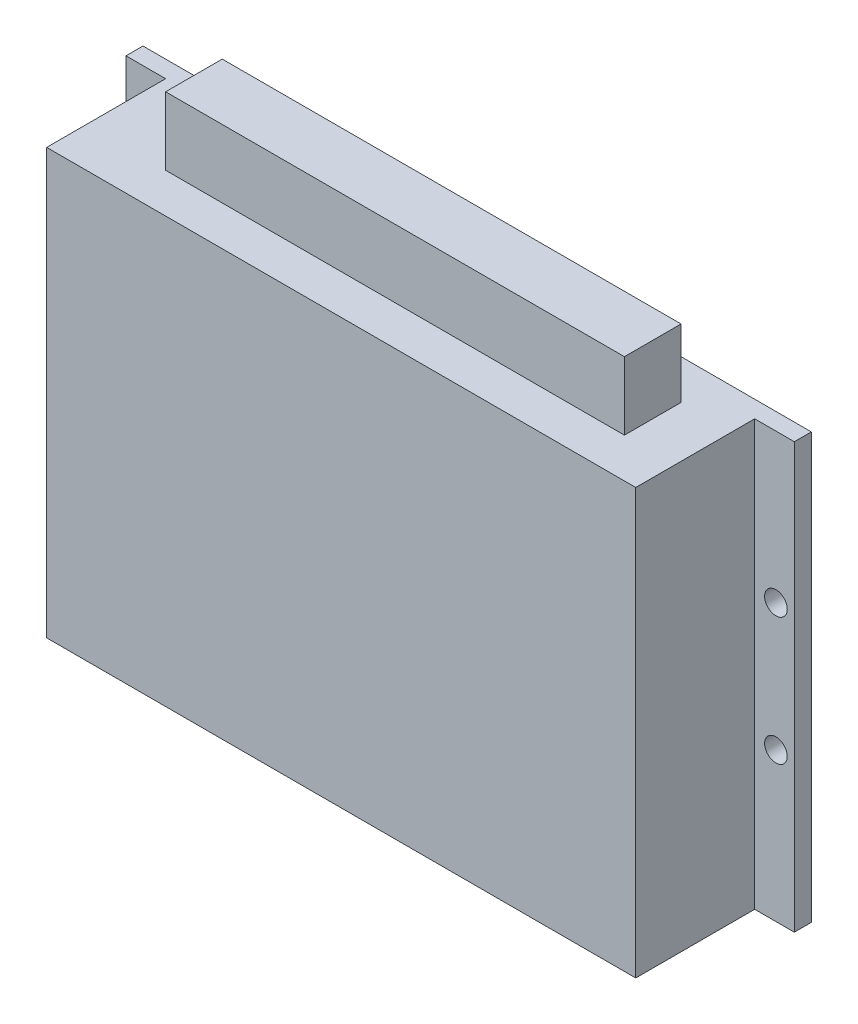
SolidWorks part; units mm, degrees
ref_plane "Front Plane" through (0, 0, 0) normal (0, 0, 1) x (1, 0, 0)
ref_plane "Top Plane" through (0, 0, 0) normal (0, 1, 0) x (1, 0, 0)
ref_plane "Right Plane" through (0, 0, 0) normal (1, 0, 0) x (0, 0, -1)
sketch "Sketch2" plane through (0, 0, 0) normal (0, 0, 1) x (1, 0, 0)
  line L0 (0, 0) -> (0, -75)
  line L1 (0, -75) -> (118, -75)
  line L2 (118, -75) -> (118, 0)
  line L3 (118, 0) -> (102, 0)
  line L4 (102, 0) -> (102, 12)
  line L5 (102, 12) -> (21, 12)
  line L6 (21, 12) -> (21, 0)
  line L7 (21, 0) -> (0, 0)
  dimension "D1" = 118
  dimension "D2" = 75
  dimension "D3" = 12
  dimension "D4" = 16
  dimension "D5" = 21
extrude "Boss-Extrude1" add sketch "Sketch2" against normal blind 24
sketch "Sketch3" plane through (0, 0, 0) normal (0, 0, 1) x (1, 0, 0)
  line L0 (7, 0) -> (7, -75)
  line L1 (21, 0) -> (0, 0) construction
  line L2 (0, -75) -> (118, -75) construction
  line L3 (111, 0) -> (111, -75)
  line L4 (118, 0) -> (102, 0) construction
  line L5 (118, -75) -> (118, 0) construction
  line L6 (0, 0) -> (0, -75) construction
  line L7 (118, 0) -> (111, 0)
  line L8 (118, -75) -> (118, 0)
  line L9 (0, -75) -> (7, -75)
  line L10 (0, 0) -> (0, -75)
  line L11 (7, 0) -> (0, 0)
  line L12 (111, -75) -> (118, -75)
  dimension "D1" = 7
  dimension "D2" = 7
extrude "Cut-Extrude1" cut sketch "Sketch3" against normal blind 21
ref_plane "Plane1" through (0, 0, -12) normal (0, 0, 1) x (1, 0, 0)
sketch "Sketch4" plane through (0, 0, 0) normal (0, 0, 1) x (1, 0, 0)
  line L0 (102, 0) -> (102, 12) construction
  line L1 (102, 12) -> (21, 12) construction
  line L2 (21, 12) -> (21, 0) construction
  line L3 (102, 0) -> (102, 12)
  line L4 (102, 12) -> (21, 12)
  line L5 (21, 12) -> (21, 0)
  line L6 (21, 0) -> (102, 0)
extrude "Cut-Extrude2" cut sketch "Sketch4" against normal blind 7
mirror "Mirror1" about plane through (0, 0, -12) normal (0, 0, 1) of "Cut-Extrude2"
sketch "Sketch5" plane through (0, 0, -24) normal (0, 0, -1) x (-1, 0, 0)
  line L0 (-118, -37.5) -> (0, -37.5) construction
  line L1 (-118, -75) -> (-118, 0) construction
  line L2 (0, 0) -> (0, -75) construction
  line L3 (-59, 0) -> (-59, -75) construction
  line L4 (-118, 0) -> (0, 0) construction
  line L5 (0, -75) -> (-118, -75) construction
  circle A0 centre (-114.75, -26.25) radius 2
  circle A1 centre (-114.75, -48.75) radius 2
  circle A2 centre (-3.25, -48.75) radius 2
  circle A3 centre (-3.25, -26.25) radius 2
  point P16 (0, 0)
  dimension "D1" = 4
  dimension "D2" = 4
  dimension "D3" = 22.5
  dimension "D4" = 111.5
extrude "Cut-Extrude3" cut sketch "Sketch5" against normal up to surface (3 mm away) up to face at (114.5, -37.5, -21)
